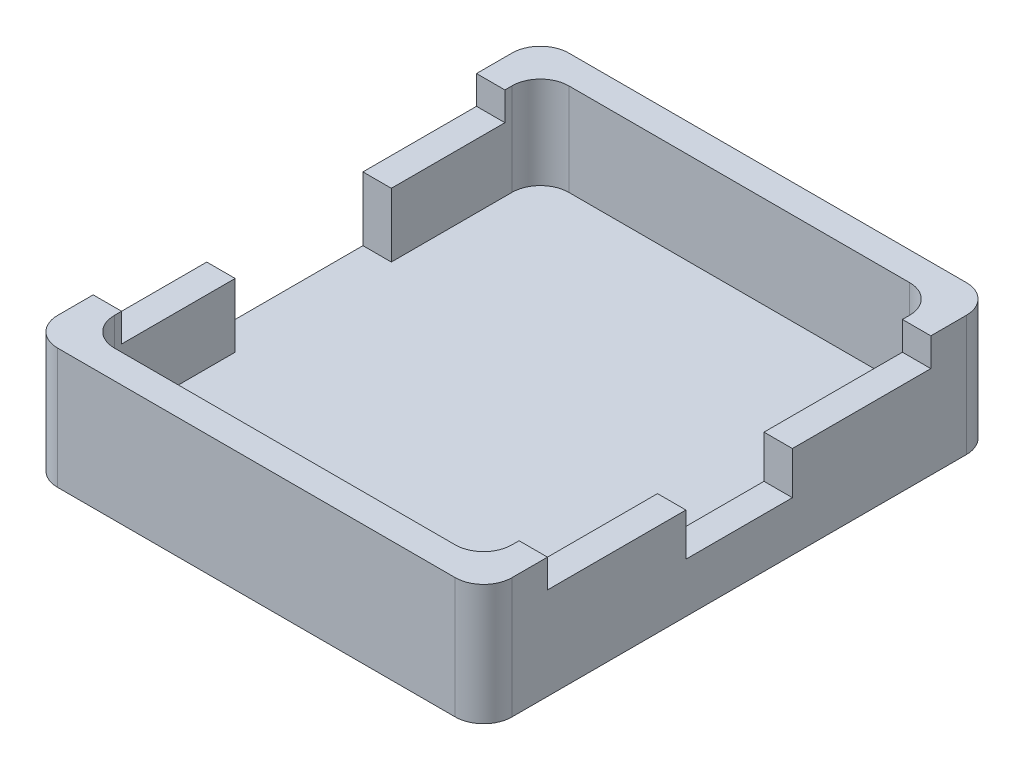
SolidWorks part; units mm, degrees
ref_plane "Front Plane" through (0, 0, 0) normal (0, 0, 1) x (1, 0, 0)
ref_plane "Top Plane" through (0, 0, 0) normal (0, 1, 0) x (1, 0, 0)
ref_plane "Right Plane" through (0, 0, 0) normal (1, 0, 0) x (0, 0, -1)
sketch "Sketch1" plane through (0, 0, 0) normal (0, 1, 0) x (1, 0, 0)
  line L0 (-16, 0) -> (16, 0) construction
  line L1 (-16, -18) -> (16, -18)
  line L2 (-16, -18) -> (-16, 18)
  line L3 (-16, 18) -> (16, 18)
  line L4 (16, -18) -> (16, 18)
  line L5 (-16, -18) -> (16, 18) construction
  line L6 (-16, 18) -> (16, -18) construction
  point P0 (0, 0)
  dimension "D1" = 32
  dimension "D2" = 36
extrude "Boss-Extrude1" add sketch "Sketch1" along normal blind 2
sketch "Sketch2" plane through (0, 2, 0) normal (0, 1, 0) x (1, 0, 0)
  line L1 (-16, 18) -> (-16, -18)
  line L20 (-16, -18) -> (16, -18)
  line L21 (-16, -18) -> (-16, 18)
  line L22 (-16, 18) -> (16, 18)
  line L23 (16, -18) -> (16, 18)
  line L24 (-16, -18) -> (16, 18) construction
  line L25 (-16, 18) -> (16, -18) construction
  line L26 (-14, -16) -> (14, -16)
  line L27 (-14, -16) -> (-14, 16)
  line L28 (-14, 16) -> (14, 16)
  line L29 (14, -16) -> (14, 16)
  line L30 (-14, -16) -> (14, 16) construction
  line L31 (-14, 16) -> (14, -16) construction
  point P0 (0, 0)
  point P9 (0, 0)
  line M13 (16, -18) -> (16, 18)
  line M14 (16, 18) -> (-16, 18)
  line M15 (-16, 18) -> (-16, -18)
  line M16 (-16, -18) -> (16, -18)
  dimension "D1" = 2
  dimension "D2" = 2
extrude "Boss-Extrude2" add sketch "Sketch2" along normal blind 6.5 contours L29 L26 L27 L28 M16 M13 M14 M15
sketch "Sketch3" plane through (-16, 0, 0) normal (-1, 0, 0) x (0, 0, 1)
  line L0 (0, 0) -> (0, 8.5) construction
  line L1 (-18, 0) -> (18, 0) construction
  line L2 (-18, 8.5) -> (18, 8.5) construction
  line L3 (-13.5, 8.5) -> (-13.5, 6.5)
  line L4 (-13.5, 6.5) -> (-5.5, 6.5)
  line L5 (-5.5, 6.5) -> (-5.5, 2)
  line L6 (-5.5, 2) -> (5.5, 2)
  line L7 (-18, 8.5) -> (-18, 0) construction
  line L8 (5.5, 6.5) -> (5.5, 2)
  line L9 (13.5, 6.5) -> (5.5, 6.5)
  line L10 (13.5, 8.5) -> (13.5, 6.5)
  line L11 (-13.5, 8.5) -> (13.5, 8.5)
  point P14 (0, 2)
  dimension "D1" = 2
  dimension "D2" = 4.5
  dimension "D3" = 5.5
  dimension "D4" = 6.5
extrude "Cut-Extrude1" cut sketch "Sketch3" against normal up to surface (2 mm away) up to face at (-14, 5.25, 0)
sketch "Sketch4" plane through (16, 0, 0) normal (1, 0, 0) x (0, 0, -1)
  line L0 (0, 0) -> (0, 8.5) construction
  line L1 (-18, 8.5) -> (18, 8.5) construction
  line L2 (-13.5, 8.5) -> (-13.5, 6.5)
  line L3 (-13.5, 6.5) -> (-3.75, 6.5)
  line L4 (-3.75, 6.5) -> (-3.75, 3.5)
  line L5 (-3.75, 3.5) -> (3.75, 3.5)
  line L6 (-18, 8.5) -> (-18, 0) construction
  line L7 (3.75, 6.5) -> (3.75, 3.5)
  line L8 (13.5, 6.5) -> (3.75, 6.5)
  line L9 (13.5, 8.5) -> (13.5, 6.5)
  line L10 (-13.5, 8.5) -> (13.5, 8.5)
  point P13 (0, 3.5)
  dimension "D1" = 2
  dimension "D2" = 4.5
  dimension "D3" = 7.5
  dimension "D4" = 5
extrude "Cut-Extrude2" cut sketch "Sketch4" against normal up to surface (2 mm away) up to face at (14, 5.25, 0)
fillet "Fillet1" radius 2 8 edges at (-14, 5.25, 16) (-14, 5.25, -16) (14, 5.25, -16) (14, 5.25, 16) (-16, 4.25, 18) (-16, 4.25, -18) (16, 4.25, -18) (16, 4.25, 18)
